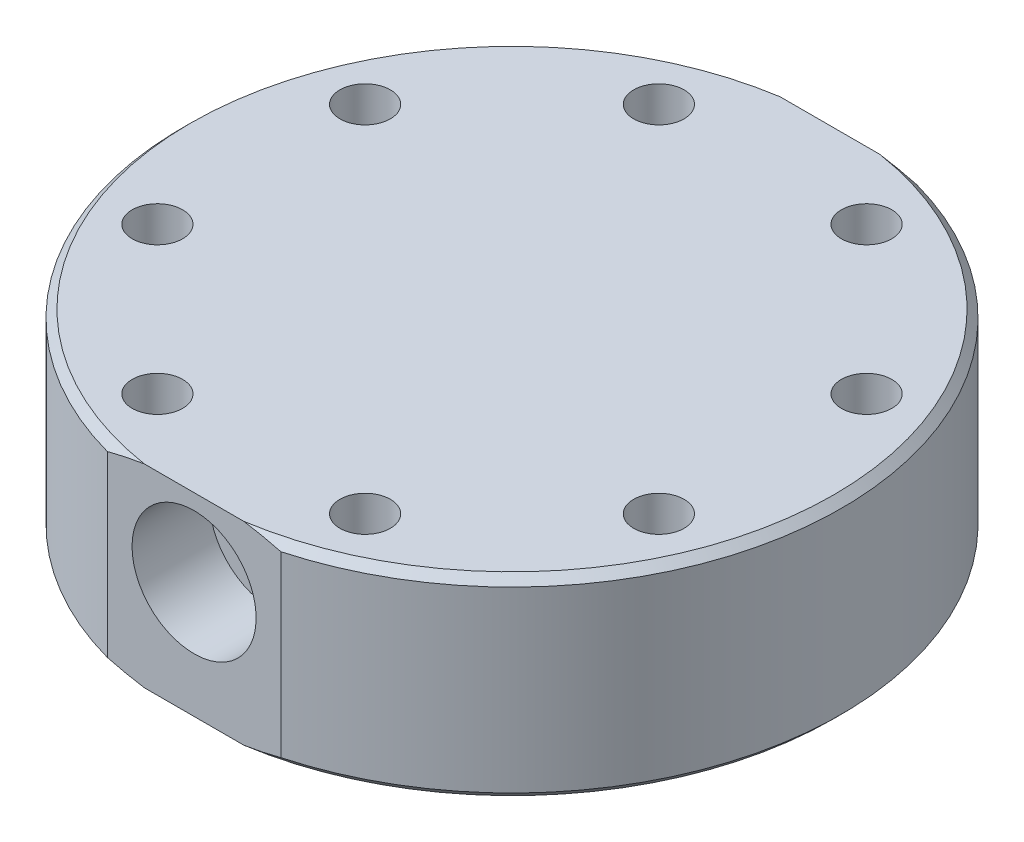
SolidWorks part; units mm, degrees
ref_plane "前基準面" through (0, 0, 0) normal (0, 0, 1) x (1, 0, 0)
ref_plane "上基準面" through (0, 0, 0) normal (0, 1, 0) x (1, 0, 0)
ref_plane "右基準面" through (0, 0, 0) normal (1, 0, 0) x (0, 0, -1)
sketch "草圖1" plane through (0, 0, 0) normal (0, 1, 0) x (1, 0, 0)
  circle A0 centre (0, 0) radius 85
  dimension "D1" = 170
extrude "填料-伸長1" add sketch "草圖1" along normal blind 50
hole_wizard "M14x1.5 螺紋孔1" positions "草圖3" profile "草圖2" tap size "M14x1.5" standard "ISO"
sketch "草圖3" plane through (0, 0, 0) normal (0, -1, 0) x (1, 0, 0)
  line L0 (-1000, 0) -> (49000, 0) construction
  line L1 (0, -1000) -> (0, 49000) construction
  point P0 (43, -27)
  point P1 (43, 27)
  point P3 (-43, 27)
  point P5 (-43, -27)
  dimension "D1" = 86
  dimension "D2" = 54
sketch "草圖2" plane through (43, 0, -27) normal (1, 0, 0) x (0, 0, -1)
  line L0 (0, 0) -> (0, 38.2554)
  line L1 (0, 38.2554) -> (6.25, 34.5)
  line L2 (6.25, 34.5) -> (6.25, 0)
  line L5 (6.25, 0) -> (0, 0)
  line L10 (0, 38.2554) -> (-6.25, 34.5) construction
  line L11 (0, -6.35) -> (0, 107.95) construction
  dimension "螺孔鑽直徑" = 12.5
  dimension "螺孔鑽深度" = 34.5
  dimension "導頭角度" = 118
cosmetic thread "鑽孔螺紋1" parameters "D1"=30, "D2"=14
cosmetic thread "鑽孔螺紋2" parameters "D1"=30, "D2"=14
cosmetic thread "鑽孔螺紋3" parameters "D1"=30, "D2"=14
cosmetic thread "鑽孔螺紋4" parameters "D1"=30, "D2"=14
hole_wizard "M12 六角頭螺栓的柱孔1" positions "草圖5" profile "草圖4" counterbore size "M12" standard "Ansi 公制" end condition through all
sketch "草圖5" plane through (0, 0, 0) normal (0, -1, 0) x (1, 0, 0)
  line L0 (-85, 0) -> (85, 0) construction
  line L2 (0, 0) -> (-64.6716, 26.7878) construction
  circle A0 centre (0, 0) radius 70 construction
  circle A1 centre (0, 0) radius 85 construction
  point P0 (-64.6716, 26.7878)
  dimension "D1" = 140
  dimension "D2" = 22.5
sketch "草圖4" plane through (-64.6716, 0, 26.7878) normal (1, 0, 0) x (0, 0, -1)
  line L0 (0, 0) -> (0, 50)
  line L1 (0, 50) -> (6.5, 50)
  line L3 (6.5, 50) -> (6.5, 15)
  line L4 (6.5, 15) -> (11, 15)
  line L5 (11, 15) -> (11, 0)
  line L7 (11, 0) -> (0, 0)
  line L11 (0, -6.35) -> (0, 107.95) construction
  dimension "貫穿孔直徑" = 13
  dimension "貫穿孔深度" = 50
  dimension "柱孔直徑" = 22
  dimension "柱孔深度" = 15
pattern_circular "環狀複製排列1" count 8 over 360 about axis through (0, 0, 0) along (0, 1, 0) of "M12 六角頭螺栓的柱孔1"
sketch "草圖6" plane through (0, 50, 0) normal (0, 1, 0) x (1, 0, 0)
  line L0 (-1000, 0) -> (49000, 0) construction
  line L2 (-22.383, 82) -> (22.383, 82)
  line L3 (-22.383, 82) -> (-22.383, 91.0838)
  line L4 (-22.383, 91.0838) -> (22.383, 91.0838)
  line L5 (22.383, 82) -> (22.383, 91.0838)
  line L6 (-22.383, -82) -> (22.383, -82)
  line L7 (-22.383, -82) -> (-22.383, -90.1474)
  line L8 (-22.383, -90.1474) -> (22.383, -90.1474)
  line L9 (22.383, -82) -> (22.383, -90.1474)
  circle A0 centre (0, 0) radius 85 construction
  dimension "D1" = 164
extrude "除料-伸長1" cut sketch "草圖6" against normal through all
sketch "草圖7" plane through (0, 0, -82) normal (0, 0, -1) x (-1, 0, 0)
  line L0 (0, -1000) -> (0, 49000) construction
  line L1 (22.383, 0) -> (-22.383, 0) construction
  circle A0 centre (0, 30) radius 16
  point P5 (0, 0)
  dimension "D1" = 32
  dimension "D2" = 30
extrude "除料-伸長2" cut sketch "草圖7" against normal blind 20
mirror "鏡射1" about plane through (0, 0, 0) normal (0, 0, 1) of "除料-伸長2"
sketch "草圖8" plane through (0, 0, 62) normal (0, 0, 1) x (1, 0, 0)
  circle A0 centre (0, 30) radius 9
  dimension "D1" = 18
extrude "除料-伸長3" cut sketch "草圖8" against normal through all
chamfer "導角1" distance 2 angle 45 4 edges at (85, 0, 0) (-85, 0, 0) (85, 50, 0) (-85, 50, 0)
chamfer "導角2" distance 0.5 angle 45 4 edges at (-43, 0, 20.75) (-26.7878, 0, -75.6716) (43, 0, -33.25) (43, 0, 20.75)
